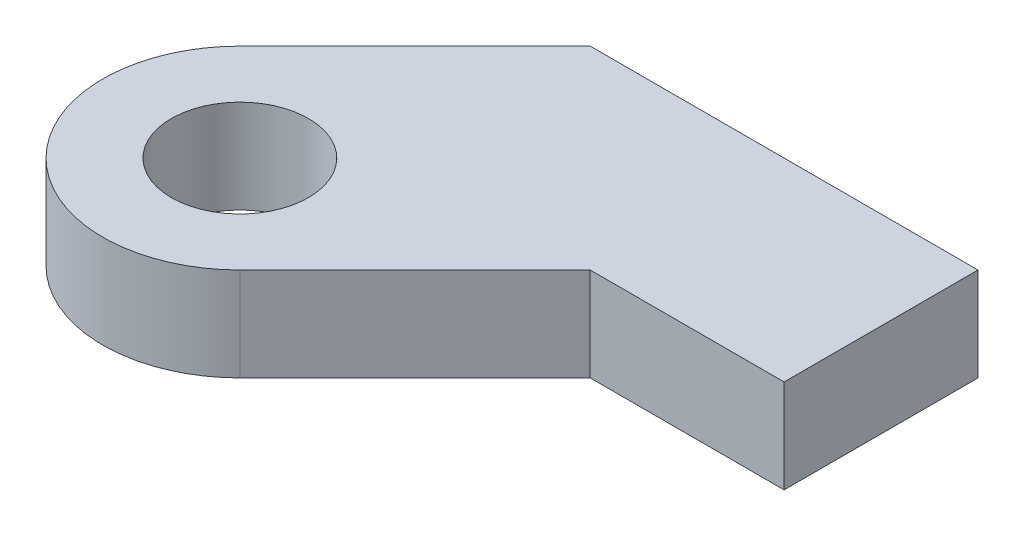
SolidWorks part; units mm, degrees
material "Zoltek Panex 33"
ref_plane "前视基准面" through (0, 0, 0) normal (0, 0, 1) x (1, 0, 0)
ref_plane "上视基准面" through (0, 0, 0) normal (0, 1, 0) x (1, 0, 0)
ref_plane "右视基准面" through (0, 0, 0) normal (1, 0, 0) x (0, 0, -1)
sketch "草图2" plane through (0, 0, 0) normal (0, 1, 0) x (1, 0, 0)
  line L4 (0, 0) -> (2.175, 0) construction
  line L5 (0, 0) -> (0, 2.175) construction
  line L6 (0, 2.175) -> (2.175, 0) construction
  line L7 (0, 0) -> (1.0875, 1.0875) construction
  line L8 (1.0875, 1.0875) -> (1.538, 1.538) construction
  line L9 (1.538, 1.538) -> (4.6492, 1.538)
  line L11 (4.6492, 1.538) -> (4.6492, -1.5733)
  line L12 (1.538, -1.5733) -> (4.6492, -1.5733)
  line L13 (0, 0) -> (-2.8284, -2.8284) construction
  line L14 (1.538, -1.5733) -> (-1.2728, -4.3841)
  line L15 (-1.5733, 1.538) -> (-4.3841, -1.2728)
  line L16 (1.538, 1.538) -> (-1.5733, 1.538)
  arc A5 (-4.3841, -1.2728) -> (-1.2728, -4.3841) centre (-2.8284, -2.8284) ccw
  circle A6 centre (-2.8284, -2.8284) radius 1.1
  point P8 (-4.8943, -4.8943)
  dimension "D1" = 2.2
  dimension "D2" = 4
  dimension "D3" = 2.2
  dimension "D4" = 4.4
extrude "凸台-拉伸1" add sketch "草图2" along normal blind 1.5
